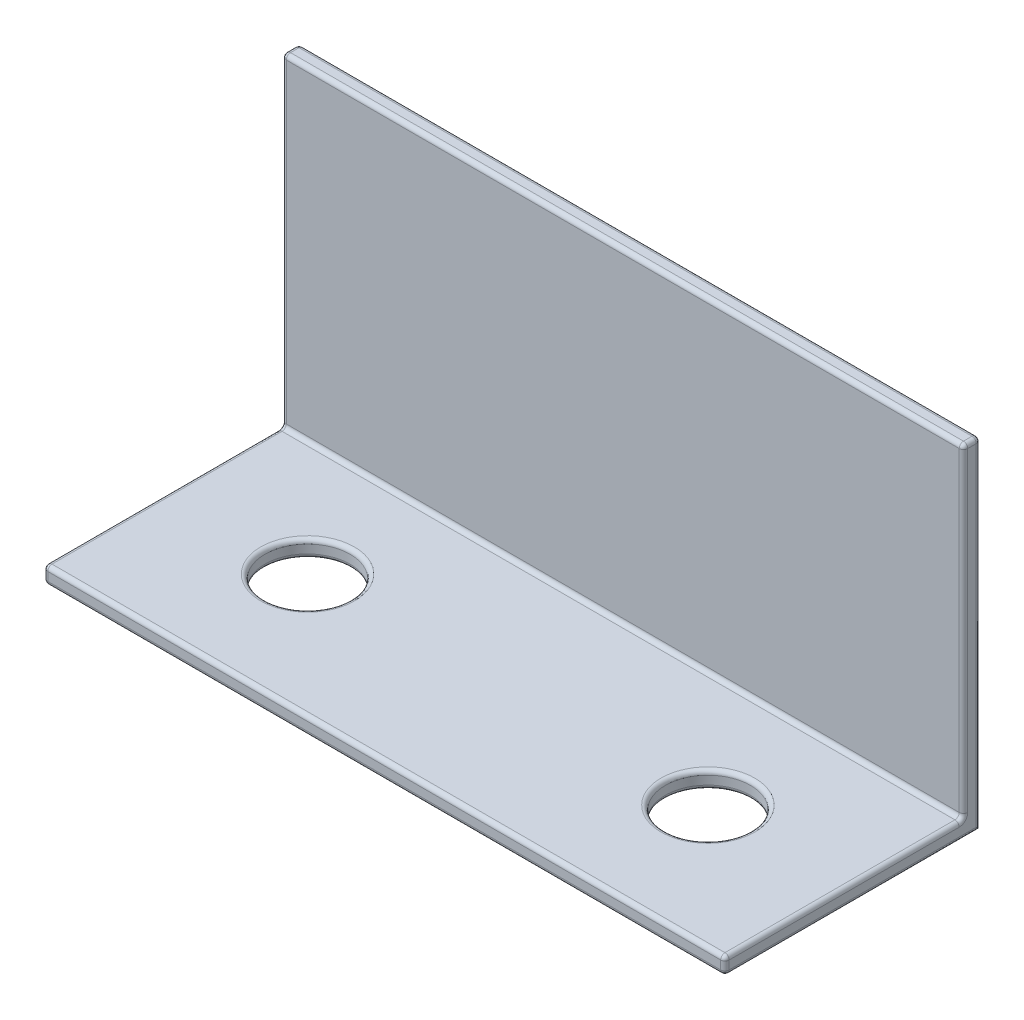
SolidWorks part; units mm, degrees
ref_plane "Front Plane" through (0, 0, 0) normal (0, 0, 1) x (1, 0, 0)
ref_plane "Top Plane" through (0, 0, 0) normal (0, 1, 0) x (1, 0, 0)
ref_plane "Right Plane" through (0, 0, 0) normal (1, 0, 0) x (0, 0, -1)
sketch "Sketch1" plane through (0, 0, 0) normal (1, 0, 0) x (0, 0, -1)
  line L0 (0, 0) -> (14, 0)
  line L1 (14, 0) -> (14, 19)
  line L2 (14, 19) -> (15, 19)
  line L3 (15, 19) -> (15, -1)
  line L4 (15, -1) -> (0, -1)
  line L5 (0, -1) -> (0, 0)
  dimension "D1" = 15
  dimension "D2" = 20
  dimension "D3" = 1
  dimension "D4" = 1
extrude "Boss-Extrude1" add sketch "Sketch1" along normal blind 40
fillet "Fillet1" radius 0.25 17 edges at (0, -1, -7.5) (0, 9, -15) (0, 9.5, -14) (0, 0, -7) (20, 19, -15) (20, 19, -14) (0, 19, -14.5) (40, 0, -7) (40, 9.5, -14) (40, 19, -14.5) (40, 9, -15) (40, -1, -7.5) (20, 0, 0) (40, -0.5, 0) (20, -1, 0) (0, -0.5, 0) (20, 0, -14)
sketch "Sketch2" plane through (0, 0, 0) normal (0, 1, 0) x (1, 0, 0)
  line L0 (20, 0.25) -> (20, 31.7261) construction
  line L1 (0.25, 0.25) -> (39.75, 0.25) construction
  line L2 (0.25, 13.75) -> (0.25, 0.25) construction
  circle A0 centre (8.25, 7.25) radius 2.5
  circle A2 centre (31.75, 7.25) radius 2.5
  dimension "D1" = 5
  dimension "D2" = 7
  dimension "D3" = 8
extrude "Cut-Extrude1" cut sketch "Sketch2" against normal up to next
fillet "Fillet2" radius 0.25 4 edges at (31.75, -1, -4.75) (8.25, -1, -4.75) (8.25, 0, -4.75) (31.75, 0, -9.75)
